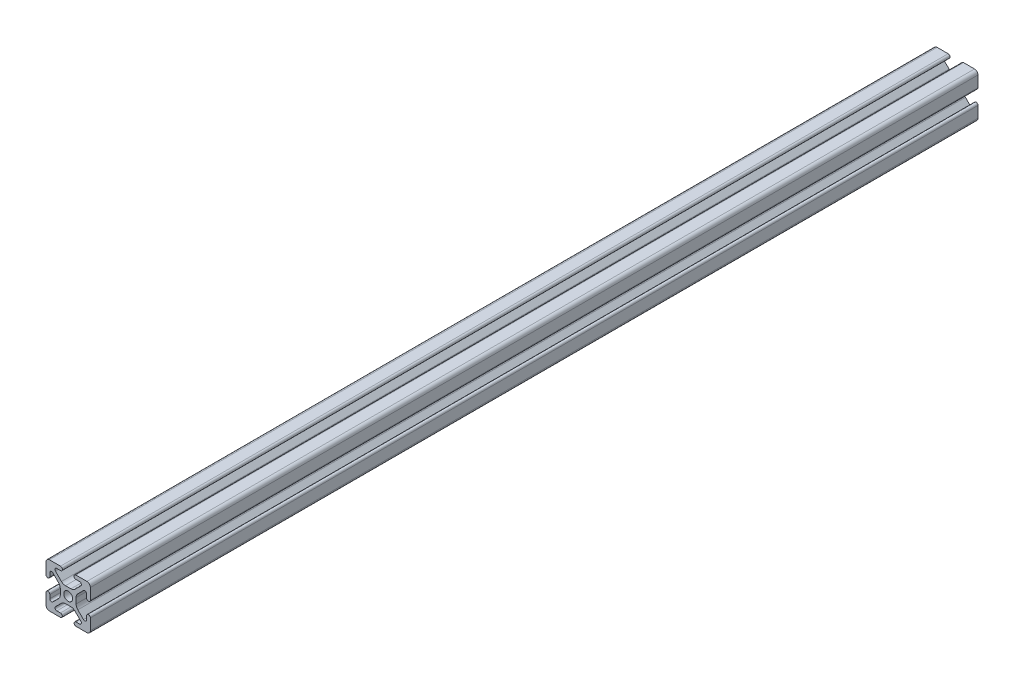
SolidWorks part; units mm, degrees
ref_plane "Front Plane" through (0, 0, 0) normal (0, 0, 1) x (1, 0, 0)
ref_plane "Top Plane" through (0, 0, 0) normal (0, 1, 0) x (1, 0, 0)
ref_plane "Right Plane" through (0, 0, 0) normal (1, 0, 0) x (0, 0, -1)
ref_plane "Plane1" through (0, 0, -4000) normal (0, 0, -1) x (-1, 0, 0)
sketch "Sketch1" plane through (0, 0, -4000) normal (0, 0, -1) x (-1, 0, 0)
  line L0 (12.5, 4.32) -> (12.5, 10.5371)
  line L1 (10.5371, 12.5) -> (4.32, 12.5)
  line L2 (4.32, 10.36) -> (6.42, 10.36)
  line L3 (7.1337, 8.6353) -> (3.7953, 5.3018)
  line L4 (1.5554, 4.375) -> (-1.5554, 4.375)
  line L5 (-3.7953, 5.3018) -> (-7.1337, 8.6353)
  line L6 (-6.42, 10.36) -> (-4.32, 10.36)
  line L7 (-4.32, 12.5) -> (-10.5371, 12.5)
  line L8 (-12.5, 10.5371) -> (-12.5, 4.32)
  line L9 (-10.36, 4.32) -> (-10.36, 6.3969)
  line L10 (-8.6363, 7.1116) -> (-5.4322, 3.9121)
  line L11 (-4.455, 1.5554) -> (-4.455, -1.5554)
  line L12 (-5.4322, -3.9121) -> (-8.6363, -7.1116)
  line L13 (-10.36, -6.3969) -> (-10.36, -4.32)
  line L14 (-12.5, -4.32) -> (-12.5, -10.5371)
  line L15 (-10.5371, -12.5) -> (-4.3879, -12.5)
  line L16 (-4.3879, -10.36) -> (-6.42, -10.36)
  line L17 (-7.1337, -8.6353) -> (-3.7953, -5.3018)
  line L18 (-1.5554, -4.375) -> (1.5554, -4.375)
  line L19 (3.7953, -5.3018) -> (7.1337, -8.6353)
  line L20 (6.42, -10.36) -> (4.3879, -10.36)
  line L21 (4.3879, -12.5) -> (10.5371, -12.5)
  line L22 (12.5, -10.5371) -> (12.5, -4.32)
  line L23 (10.36, -4.32) -> (10.36, -6.3969)
  line L24 (8.6363, -7.1116) -> (5.4322, -3.9121)
  line L25 (4.455, -1.5554) -> (4.455, 1.5554)
  line L26 (5.4322, 3.9121) -> (8.6363, 7.1116)
  line L27 (10.36, 6.3969) -> (10.36, 4.32)
  circle A0 centre (0, 0) radius 2.5
  arc A1 (12.5, 10.5371) -> (10.5371, 12.5) centre (10.5371, 10.5371) ccw
  arc A2 (4.32, 12.5) -> (4.32, 10.36) centre (4.32, 11.43) ccw
  arc A3 (6.42, 10.36) -> (7.1337, 8.6353) centre (6.42, 9.35) cw
  arc A4 (3.7953, 5.3018) -> (1.5554, 4.375) centre (1.5554, 7.545) cw
  arc A5 (-1.5554, 4.375) -> (-3.7953, 5.3018) centre (-1.5554, 7.545) cw
  arc A6 (-7.1337, 8.6353) -> (-6.42, 10.36) centre (-6.42, 9.35) cw
  arc A7 (-4.32, 10.36) -> (-4.32, 12.5) centre (-4.32, 11.43) ccw
  arc A8 (-10.5371, 12.5) -> (-12.5, 10.5371) centre (-10.5371, 10.5371) ccw
  arc A9 (-12.5, 4.32) -> (-10.36, 4.32) centre (-11.43, 4.32) ccw
  arc A10 (-10.36, 6.3969) -> (-8.6363, 7.1116) centre (-9.35, 6.3969) cw
  arc A11 (-5.4322, 3.9121) -> (-4.455, 1.5554) centre (-7.7855, 1.5554) cw
  arc A12 (-4.455, -1.5554) -> (-5.4322, -3.9121) centre (-7.7855, -1.5554) cw
  arc A13 (-8.6363, -7.1116) -> (-10.36, -6.3969) centre (-9.35, -6.3969) cw
  arc A14 (-10.36, -4.32) -> (-12.5, -4.32) centre (-11.43, -4.32) ccw
  arc A15 (-12.5, -10.5371) -> (-10.5371, -12.5) centre (-10.5371, -10.5371) ccw
  arc A16 (-4.3879, -12.5) -> (-4.3879, -10.36) centre (-4.3879, -11.43) ccw
  arc A17 (-6.42, -10.36) -> (-7.1337, -8.6353) centre (-6.42, -9.35) cw
  arc A18 (-3.7953, -5.3018) -> (-1.5554, -4.375) centre (-1.5554, -7.545) cw
  arc A19 (1.5554, -4.375) -> (3.7953, -5.3018) centre (1.5554, -7.545) cw
  arc A20 (7.1337, -8.6353) -> (6.42, -10.36) centre (6.42, -9.35) cw
  arc A21 (4.3879, -10.36) -> (4.3879, -12.5) centre (4.3879, -11.43) ccw
  arc A22 (10.5371, -12.5) -> (12.5, -10.5371) centre (10.5371, -10.5371) ccw
  arc A23 (12.5, -4.32) -> (10.36, -4.32) centre (11.43, -4.32) ccw
  arc A24 (10.36, -6.3969) -> (8.6363, -7.1116) centre (9.35, -6.3969) cw
  arc A25 (5.4322, -3.9121) -> (4.455, -1.5554) centre (7.7855, -1.5554) cw
  arc A26 (4.455, 1.5554) -> (5.4322, 3.9121) centre (7.7855, 1.5554) cw
  arc A27 (8.6363, 7.1116) -> (10.36, 6.3969) centre (9.35, 6.3969) cw
  arc A28 (10.36, 4.32) -> (12.5, 4.32) centre (11.43, 4.32) ccw
extrude "Boss-Extrude1" add sketch "Sketch1" against normal blind 500
